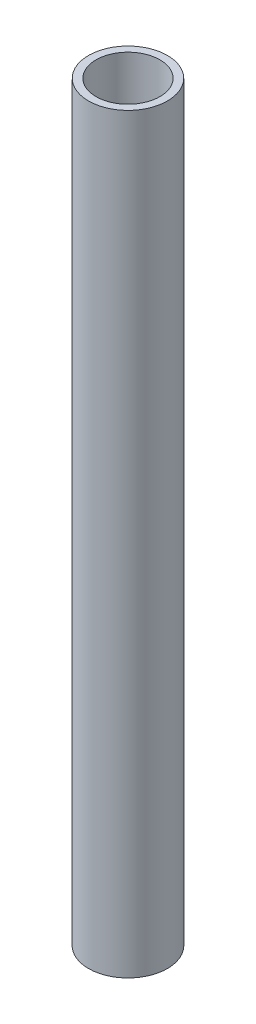
SolidWorks part; units mm, degrees
ref_plane "Front Plane" through (0, 0, 0) normal (0, 0, 1) x (1, 0, 0)
ref_plane "Top Plane" through (0, 0, 0) normal (0, 1, 0) x (1, 0, 0)
ref_plane "Right Plane" through (0, 0, 0) normal (1, 0, 0) x (0, 0, -1)
sketch "Sketch1" plane through (0, 0, 0) normal (0, 1, 0) x (1, 0, 0)
  circle A0 centre (0, 0) radius 10.5
  circle A1 centre (0, 0) radius 8.5
  dimension "D1" = 21
  dimension "D2" = 17
extrude "Boss-Extrude1" add sketch "Sketch1" along normal blind 200
